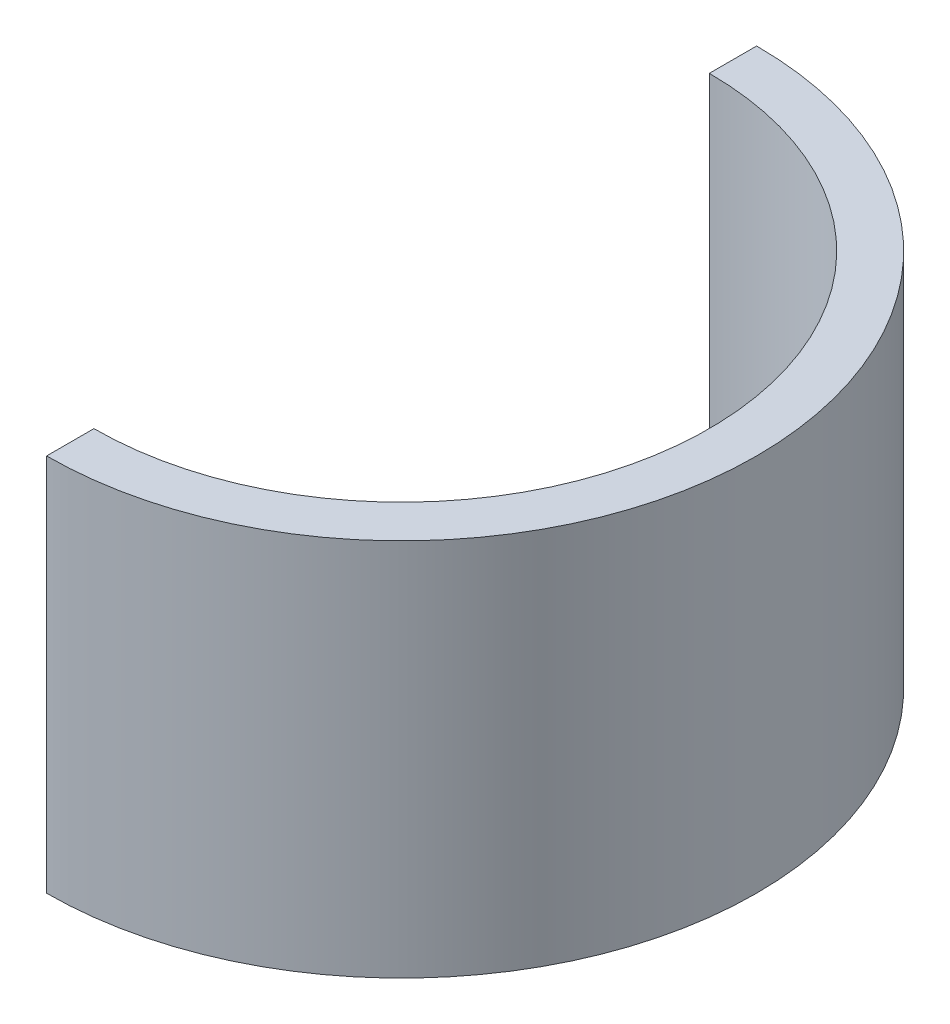
SolidWorks part; units mm, degrees
ref_plane "Front Plane" through (0, 0, 0) normal (0, 0, 1) x (1, 0, 0)
ref_plane "Top Plane" through (0, 0, 0) normal (0, 1, 0) x (1, 0, 0)
ref_plane "Right Plane" through (0, 0, 0) normal (1, 0, 0) x (0, 0, -1)
sketch "Sketch1" plane through (0, 0, 0) normal (0, 1, 0) x (1, 0, 0)
  line L0 (0, 7.5) -> (0, 6.5)
  line L1 (0, -6.5) -> (0, -7.5)
  arc A0 (0, -6.5) -> (0, 6.5) centre (0, 0) ccw
  arc A1 (0, -7.5) -> (0, 7.5) centre (0, 0) ccw
  circle A2 centre (0, 0) radius 7.5 construction
  circle A3 centre (0, 0) radius 6.5 construction
  dimension "D1" = 13
  dimension "D2" = 1
extrude "Boss-Extrude1" add sketch "Sketch1" along normal blind 8
